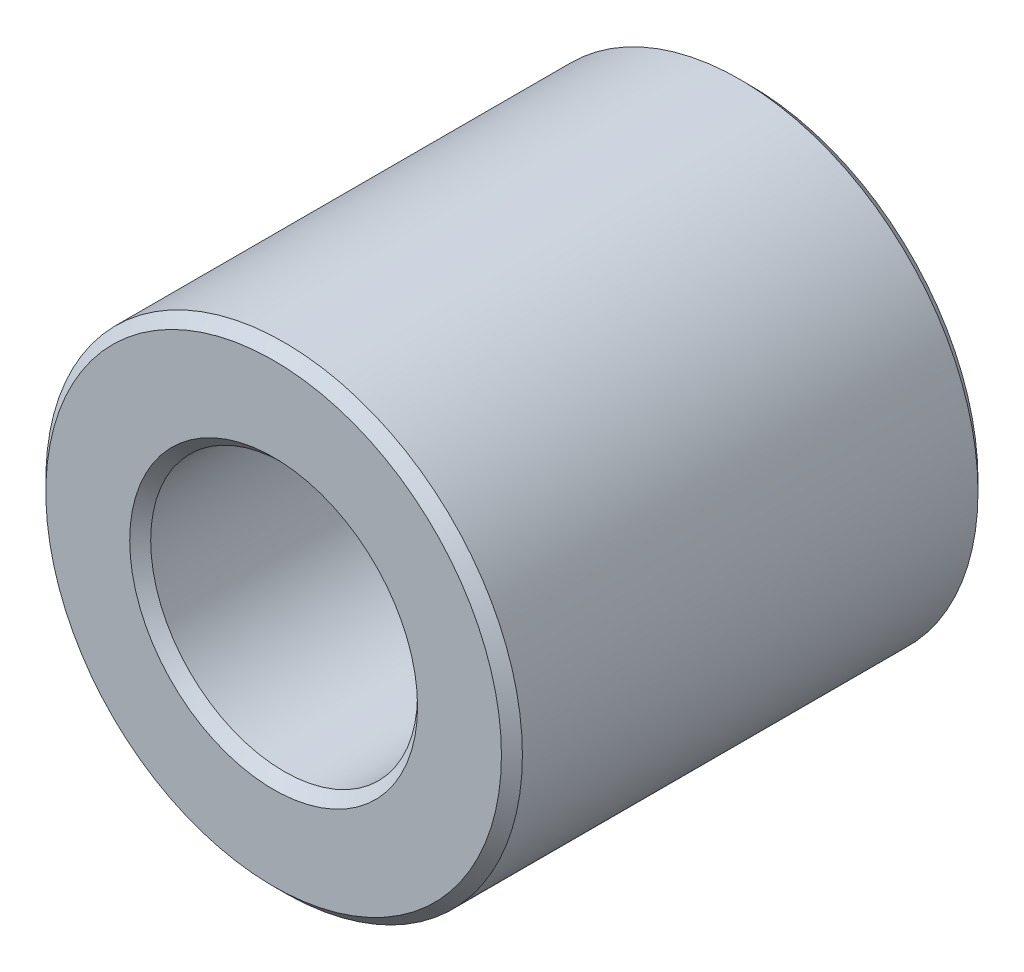
SolidWorks part; units mm, degrees
ref_plane "Front Plane" through (0, 0, 0) normal (0, 0, 1) x (1, 0, 0)
ref_plane "Top Plane" through (0, 0, 0) normal (0, 1, 0) x (1, 0, 0)
ref_plane "Right Plane" through (0, 0, 0) normal (1, 0, 0) x (0, 0, -1)
sketch "Sketch1" plane through (0, 0, 0) normal (0, 0, 1) x (1, 0, 0)
  circle A0 centre (0, 0) radius 3.175 construction
  circle A1 centre (0, 0) radius 1.778 construction
  point P4 (0, 3.175)
  dimension "ID" = 3.556
  dimension "OD" = 6.35
sketch "Sketch2" plane through (0, 0, 0) normal (1, 0, 0) x (0, 0, -1)
  line L0 (-3.175, 3.175) -> (3.175, 3.175) construction
  dimension "Length" = 6.35
sketch "Sketch3" plane through (0, 0, 0) normal (0, 0, 1) x (1, 0, 0)
  circle A0 centre (0, 0) radius 1.778 construction
  circle A1 centre (0, 0) radius 3.175 construction
  circle A2 centre (0, 0) radius 1.778
  circle A3 centre (0, 0) radius 3.175
extrude "Boss-Extrude1" add sketch "Sketch3" against normal up to vertex (3.175 mm away) and the other way up to vertex (3.175 mm away) up to point (0, 3.175, -3.175) other way up to point (0, 3.175, 3.175)
chamfer "Chamfer1" distance 0.1397 angle 45 4 edges at (3.175, 0, 3.175) (3.175, 0, -3.175) (1.778, 0, 3.175) (1.778, 0, -3.175)
equation "\"D1@Chamfer1\"=(\"OD@Sketch1\"-\"ID@Sketch1\")*0.05"
